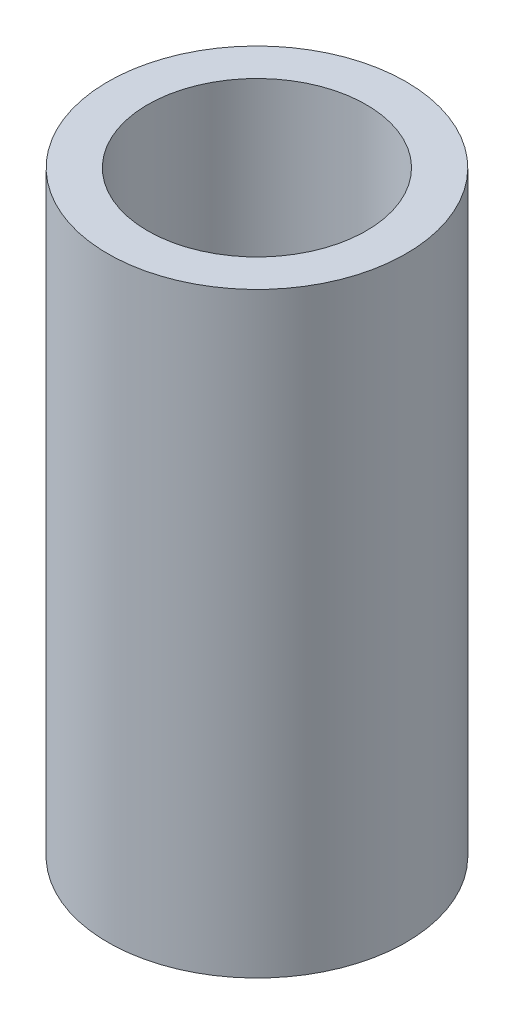
SolidWorks part; units mm, degrees
material "ABS PC"
ref_plane "Front Plane" through (0, 0, 0) normal (0, 0, 1) x (1, 0, 0)
ref_plane "Top Plane" through (0, 0, 0) normal (0, 1, 0) x (1, 0, 0)
ref_plane "Right Plane" through (0, 0, 0) normal (1, 0, 0) x (0, 0, -1)
sketch "Sketch1" plane through (0, 0, 0) normal (0, 1, 0) x (1, 0, 0)
  circle A0 centre (0, 0) radius 9.525
  dimension "D1" = 19.05
extrude "Boss-Extrude1" add sketch "Sketch1" along normal blind 38.1
sketch "Sketch2" plane through (0, 38.1, 0) normal (0, 1, 0) x (1, 0, 0)
  circle A0 centre (0, 0) radius 6.985
  circle A1 centre (0, 0) radius 9.525 construction
  dimension "D1" = 2.54
extrude "Cut-Extrude1" cut sketch "Sketch2" against normal blind 36.83
